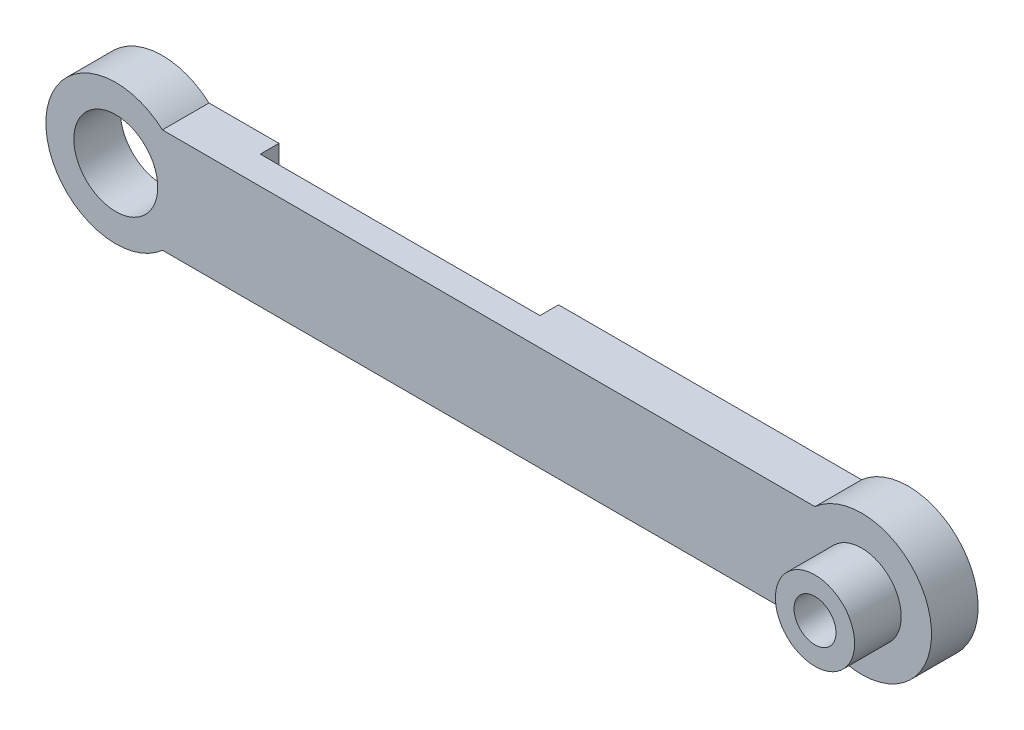
SolidWorks part; units mm, degrees
ref_plane "Front" through (0, 0, 0) normal (0, 0, 1) x (1, 0, 0)
ref_plane "Top" through (0, 0, 0) normal (0, 1, 0) x (1, 0, 0)
ref_plane "Right" through (0, 0, 0) normal (1, 0, 0) x (0, 0, -1)
sketch "스케치1" plane through (0, 0, 0) normal (0, 0, 1) x (1, 0, 0)
  line L0 (0, 0) -> (80, 0) construction
  line L1 (5, 5.5902) -> (75, 5.5902)
  line L2 (5, -5.5902) -> (75, -5.5902)
  circle A0 centre (0, 0) radius 4.5
  arc A1 (5, 5.5902) -> (5, -5.5902) centre (0, 0) ccw
  arc A2 (75, -5.5902) -> (75, 5.5902) centre (80, 0) ccw
  dimension "D1" = 9
  dimension "D2" = 15
  dimension "D3" = 15
  dimension "D4" = 70
  dimension "D5" = 80
extrude "보스-돌출1" add sketch "스케치1" along normal blind 5
sketch "스케치2" plane through (0, 0, 5) normal (0, 0, 1) x (1, 0, 0)
  circle A0 centre (80, 0) radius 4.25
  arc A1 (75, -5.5902) -> (75, 5.5902) centre (80, 0) ccw construction
  dimension "D1" = 8.5
extrude "보스-돌출2" add sketch "스케치2" along normal blind 5
sketch "스케치3" plane through (0, 0, 10) normal (0, 0, 1) x (1, 0, 0)
  circle A0 centre (80, 0) radius 2.25
  circle A1 centre (80, 0) radius 4.25 construction
  dimension "D1" = 4.5
extrude "컷-돌출1" cut sketch "스케치3" against normal blind 18
sketch "스케치4" plane through (0, 5.5902, 0) normal (0, 1, 0) x (1, 0, 0)
  line L0 (75, 0) -> (5, 0) construction
  line L1 (12.5, 0) -> (42.5, 0)
  line L2 (12.5, 0) -> (12.5, -2)
  line L3 (12.5, -2) -> (42.5, -2)
  line L4 (42.5, 0) -> (42.5, -2)
  line L5 (-7.5, 0) -> (-7.5, -5) construction
  dimension "D1" = 30
  dimension "D2" = 2
  dimension "D3" = 20
extrude "컷-돌출2" cut sketch "스케치4" against normal up to next
